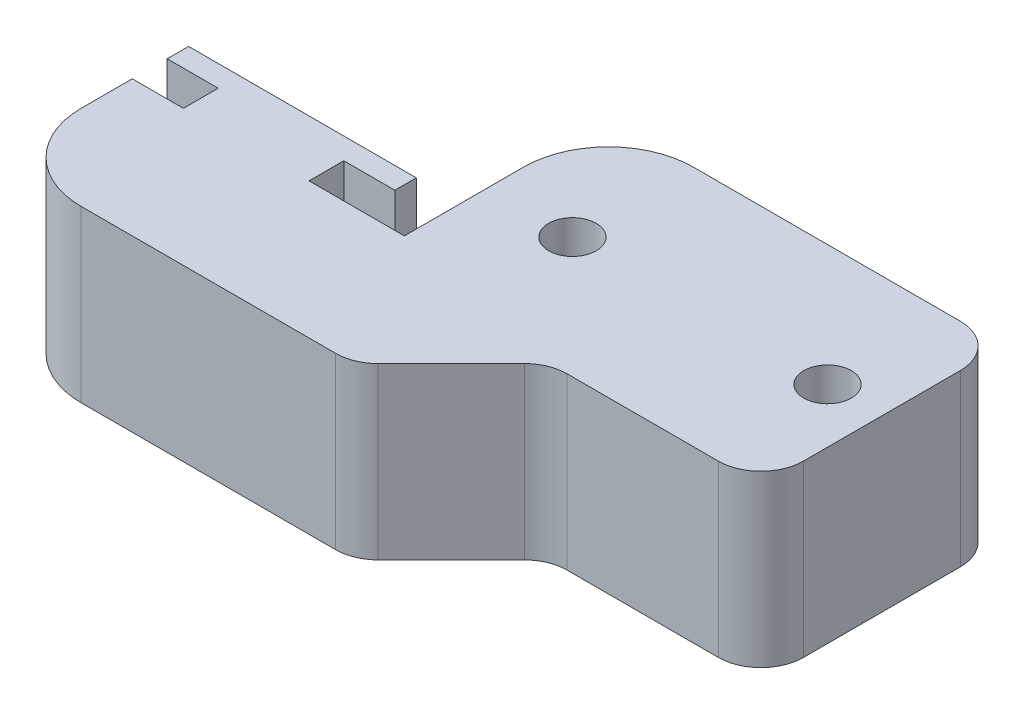
SolidWorks part; units mm, degrees
ref_plane "Front Plane" through (0, 0, 0) normal (0, 0, 1) x (1, 0, 0)
ref_plane "Top Plane" through (0, 0, 0) normal (0, 1, 0) x (1, 0, 0)
ref_plane "Right Plane" through (0, 0, 0) normal (1, 0, 0) x (0, 0, -1)
sketch "Sketch1" plane through (0, 0, 0) normal (0, 1, 0) x (1, 0, 0)
  line L0 (-32.3905, 10.3707) -> (-22.421, 10.3707)
  line L1 (-35.5655, 7.1957) -> (-35.5655, 2.7507)
  line L2 (-33.0481, -2.3293) -> (-42.5505, -2.3293)
  line L3 (-43.8155, 2.7507) -> (-45.7255, 2.7507)
  line L4 (-20.8335, 2.9182) -> (-20.8335, 8.7832)
  line L5 (-43.8155, 4.0507) -> (-45.7205, 4.0507)
  line L6 (-39.1255, 2.7507) -> (-39.1255, 4.0507)
  line L7 (-22.421, 1.3307) -> (-28.0729, 1.3307)
  line L8 (-43.8155, 2.7507) -> (-43.8155, 4.0507)
  line L9 (-35.5655, 2.7507) -> (-39.1255, 2.7507)
  line L10 (-45.7255, 0.8457) -> (-45.7255, 2.7507)
  line L11 (-29.1955, 0.8657) -> (-31.9255, -1.8644)
  line L15 (-37.2205, 4.0507) -> (-39.1255, 4.0507)
  line L16 (-37.2205, 4.0507) -> (-37.2205, 4.8507)
  line L17 (-37.2205, 4.8507) -> (-45.7205, 4.8507)
  line L18 (-45.7205, 4.0507) -> (-45.7205, 4.8507)
  arc A0 (-22.421, 1.3307) -> (-20.8335, 2.9182) centre (-22.421, 2.9182) ccw
  arc A1 (-20.8335, 8.7832) -> (-22.421, 10.3707) centre (-22.421, 8.7832) ccw
  arc A2 (-31.9255, -1.8644) -> (-33.0481, -2.3293) centre (-33.0481, -0.7418) cw
  arc A3 (-29.1955, 0.8657) -> (-28.0729, 1.3307) centre (-28.0729, -0.2568) cw
  circle A4 centre (-32.3905, 5.8507) radius 0.889
  circle A5 centre (-22.8655, 5.8507) radius 0.889
  arc A6 (-42.5505, -2.3293) -> (-45.7255, 0.8457) centre (-42.5505, 0.8457) cw
  arc A7 (-32.3905, 10.3707) -> (-35.5655, 7.1957) centre (-32.3905, 7.1957) ccw
  point P26 (-45.7205, 4.8507)
  point P33 (-45.7255, -2.3293)
  dimension "D2" = 4.52
  dimension "D10" = 1.5875
  dimension "D13" = 3.175
  dimension "D14" = 1.778
  dimension "D15" = 1.778
  dimension "D18" = 4.69
  dimension "D3" = 1.5875
  dimension "D4" = 2.032
  dimension "D5" = 4.52
  dimension "D6" = 135
  dimension "D7" = 5.08
  dimension "D8" = 14.732
  dimension "D9" = 4.445
  dimension "D11" = 1.3
  dimension "D12" = 0.8
  dimension "D16" = 9.525
  dimension "D17" = 1.905
extrude "Boss-Extrude1" add sketch "Sketch1" along normal blind 6.35
